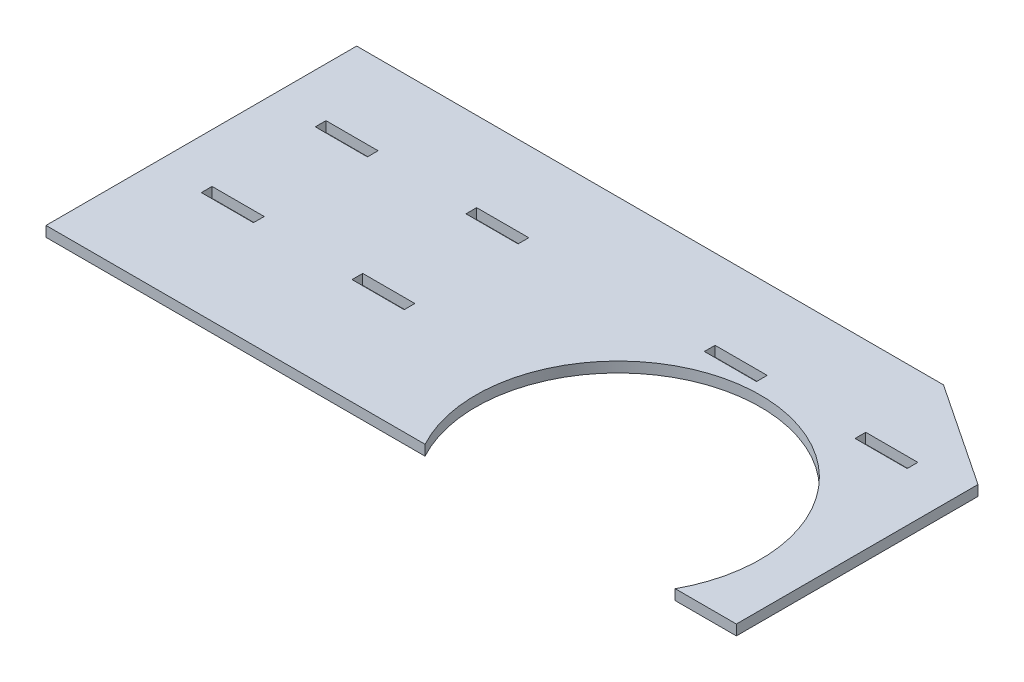
SolidWorks part; units mm, degrees
ref_plane "Front Plane" through (0, 0, 0) normal (0, 0, 1) x (1, 0, 0)
ref_plane "Top Plane" through (0, 0, 0) normal (0, 1, 0) x (1, 0, 0)
ref_plane "Right Plane" through (0, 0, 0) normal (1, 0, 0) x (0, 0, -1)
sketch "Sketch2" plane through (0, 0, 0) normal (0, 1, 0) x (1, 0, 0)
  line L0 (0, 45) -> (113.4902, 45) construction
  line L5 (0, 0) -> (109.8141, 0)
  line L26 (0, 0) -> (0, 90)
  line L27 (0, 90) -> (170, 90)
  line L28 (200, 0) -> (200, 70)
  line L29 (111.4563, 90) -> (111.4563, 42.1403) construction
  line L30 (43.645, 45) -> (43.645, 0) construction
  line L31 (14.27, 33.84) -> (29.37, 33.84)
  line L32 (14.27, 33.84) -> (14.27, 30.74)
  line L33 (14.27, 30.74) -> (29.37, 30.74)
  line L34 (29.37, 33.84) -> (29.37, 30.74)
  line L35 (73.02, 30.74) -> (57.92, 30.74)
  line L36 (57.92, 33.84) -> (57.92, 30.74)
  line L37 (73.02, 33.84) -> (57.92, 33.84)
  line L38 (73.02, 33.84) -> (73.02, 30.74)
  line L47 (43.645, 90) -> (43.645, 45) construction
  line L48 (14.27, 66.84) -> (29.37, 66.84)
  line L49 (14.27, 66.84) -> (14.27, 63.74)
  line L50 (14.27, 63.74) -> (29.37, 63.74)
  line L51 (29.37, 66.84) -> (29.37, 63.74)
  line L52 (73.02, 63.74) -> (57.92, 63.74)
  line L53 (57.92, 66.84) -> (57.92, 63.74)
  line L54 (73.02, 66.84) -> (57.92, 66.84)
  line L55 (73.02, 66.84) -> (73.02, 63.74)
  line L56 (170, 90) -> (200, 70)
  line L57 (126.99, 66.84) -> (142.09, 66.84)
  line L58 (126.99, 66.84) -> (126.99, 63.74)
  line L59 (126.99, 63.74) -> (142.09, 63.74)
  line L60 (142.09, 66.84) -> (142.09, 63.74)
  line L61 (170.64, 66.84) -> (185.74, 66.84)
  line L62 (170.64, 66.84) -> (170.64, 63.74)
  line L63 (170.64, 63.74) -> (185.74, 63.74)
  line L64 (185.74, 66.84) -> (185.74, 63.74)
  line L65 (182.2859, 0) -> (200, 0)
  line L66 (178.6098, 45) -> (200, 45) construction
  arc A0 (182.2859, 0) -> (109.8141, 0) centre (146.05, 19.69) ccw
  point P1 (200, 90)
  dimension "D20" = 82.48
  dimension "D1" = 200
  dimension "D2" = 90
  dimension "D3" = 15.1
  dimension "D4" = 3.1
  dimension "D5" = 14.27
  dimension "D6" = 30.74
  dimension "D7" = 28.55
  dimension "D8" = 15.1
  dimension "D9" = 3.1
  dimension "D10" = 29.9
  dimension "D11" = 15.1
  dimension "D12" = 3.1
  dimension "D13" = 53.97
  dimension "D14" = 15.1
  dimension "D15" = 3.1
  dimension "D16" = 28.55
  dimension "D17" = 30
  dimension "D18" = 20
  dimension "D19" = 11.05
  dimension "D21" = 73.03
extrude "Boss-Extrude2" add sketch "Sketch2" along normal blind 3
